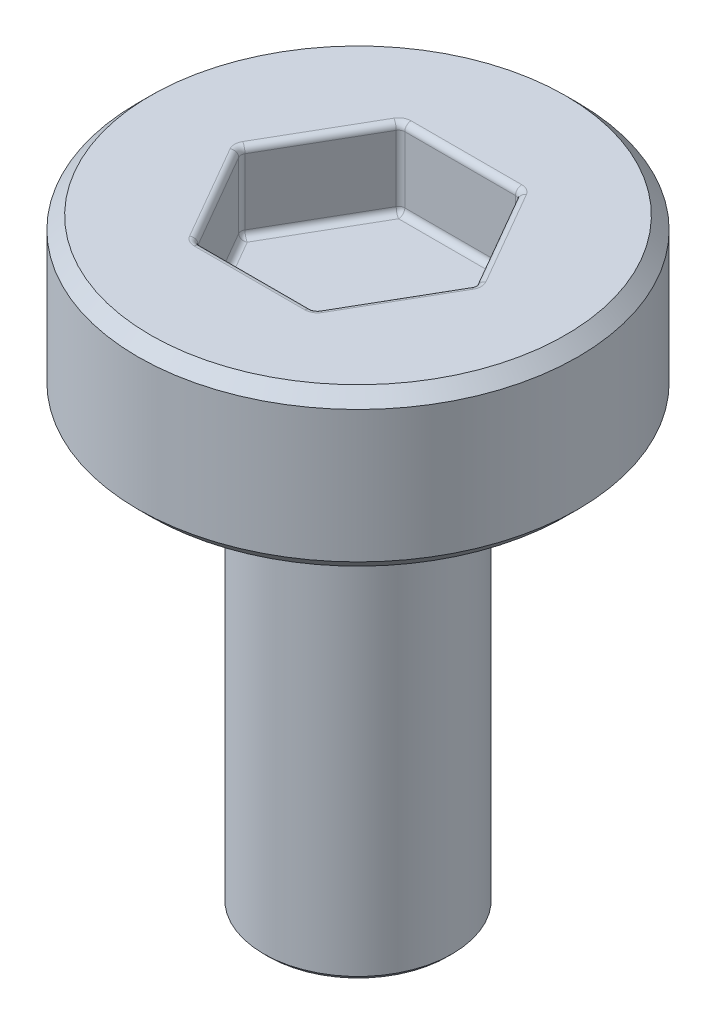
SolidWorks part; units mm, degrees
ref_plane "Front Plane" through (0, 0, 0) normal (0, 0, 1) x (1, 0, 0)
ref_plane "Top Plane" through (0, 0, 0) normal (0, 1, 0) x (1, 0, 0)
ref_plane "Right Plane" through (0, 0, 0) normal (1, 0, 0) x (0, 0, -1)
sketch "Sketch1" plane through (0, 0, 0) normal (0, 1, 0) x (1, 0, 0)
  circle A0 centre (0, 0) radius 1.5
  dimension "D1" = 3
extrude "Boss-Extrude1" add sketch "Sketch1" along normal blind 7
sketch "Sketch2" plane through (0, 7, 0) normal (0, 1, 0) x (1, 0, 0)
  circle A0 centre (0, 0) radius 3.5
  dimension "D1" = 7
extrude "Boss-Extrude2" add sketch "Sketch2" along normal blind 2.5
fillet "Fillet1" radius 0.15 1 edges at (0, 7, 1.5)
chamfer "Chamfer1" distance 0.2 angle 45 2 edges at (0, 9.5, 3.5) (0, 7, 3.5)
sketch "Sketch5" plane through (0, 9.5, 0) normal (0, 1, 0) x (1, 0, 0)
  line L1 (0.9382, 1.625) -> (-0.9382, 1.625)
  line L2 (-0.9382, 1.625) -> (-1.8764, 0)
  line L3 (-1.8764, 0) -> (-0.9382, -1.625)
  line L4 (-0.9382, -1.625) -> (0.9382, -1.625)
  line L5 (0.9382, -1.625) -> (1.8764, 0)
  line L6 (1.8764, 0) -> (0.9382, 1.625)
  circle A0 centre (0, 0) radius 1.625 construction
  dimension "D1" = 3.25
extrude "Cut-Extrude1" cut sketch "Sketch5" against normal blind 1.25
chamfer "Chamfer2" distance 0.075 angle 45 1 edges at (0, 0, 1.5)
fillet "Fillet2" radius 0.1 18 edges at (1.4073, 9.5, 0.8125) (1.4073, 8.25, 0.8125) (1.4073, 9.5, -0.8125) (1.4073, 8.25, -0.8125) (0, 9.5, -1.625) (0, 8.25, -1.625) (-1.4073, 9.5, 0.8125) (-1.4073, 8.25, 0.8125) (-1.4073, 8.25, -0.8125) (0, 8.25, 1.625) (0, 9.5, 1.625) (-1.4073, 9.5, -0.8125) (0.9382, 8.875, -1.625) (-1.8764, 8.875, 0) (-0.9382, 8.875, 1.625) (0.9382, 8.875, 1.625) (1.8764, 8.875, 0) (-0.9382, 8.875, -1.625)
sketch "Sketch4" plane through (0, 0, 0) normal (0, 0, 1) x (1, 0, 0)
  line L0 (-5.6741, 6) -> (6.8738, 6)
  dimension "D1" = 6
split line "Split Line1"
